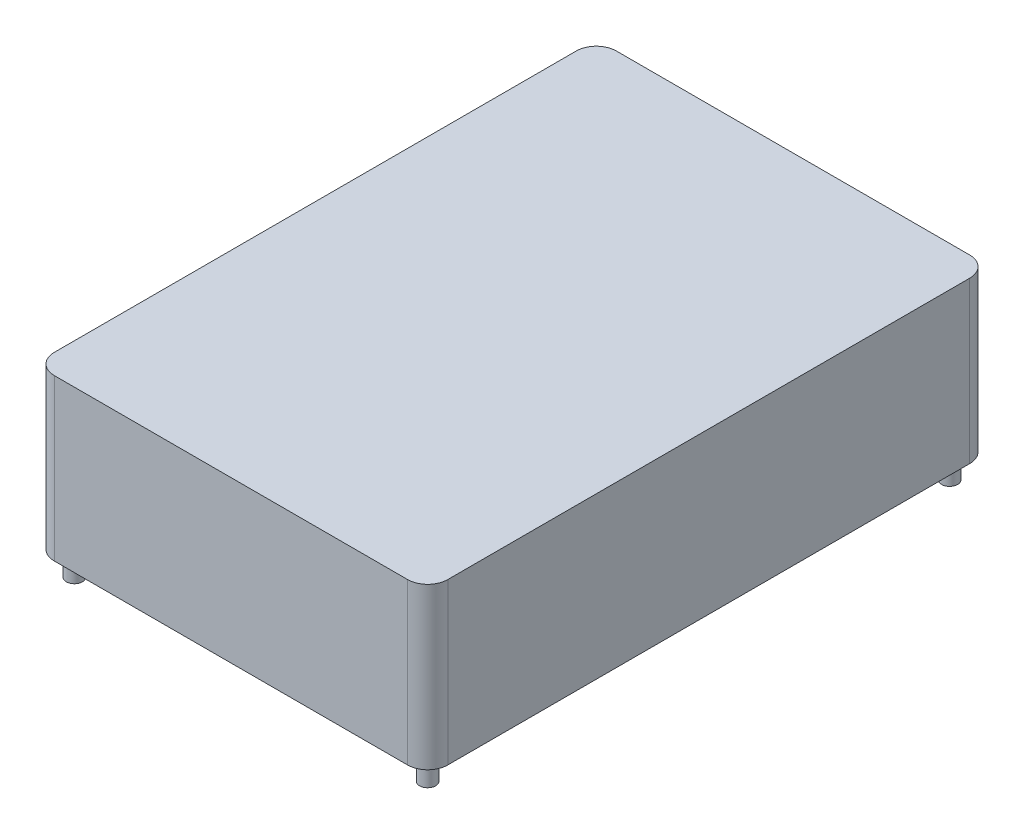
SolidWorks part; units mm, degrees
material "ABS"
ref_plane "Front Plane" through (0, 0, 0) normal (0, 0, 1) x (1, 0, 0)
ref_plane "Top Plane" through (0, 0, 0) normal (0, 1, 0) x (1, 0, 0)
ref_plane "Right Plane" through (0, 0, 0) normal (1, 0, 0) x (0, 0, -1)
sketch "Sketch1" plane through (0, 0, 0) normal (0, 1, 0) x (1, 0, 0)
  line L1 (-62.23, -88.9) -> (62.23, -88.9)
  line L2 (-62.23, -88.9) -> (-62.23, 88.9)
  line L3 (-62.23, 88.9) -> (62.23, 88.9)
  line L4 (62.23, -88.9) -> (62.23, 88.9)
  line L5 (-62.23, -88.9) -> (62.23, 88.9) construction
  line L6 (-62.23, 88.9) -> (62.23, -88.9) construction
  point P0 (0, 0)
  dimension "D1" = 124.46
  dimension "D2" = 177.8
extrude "Boss-Extrude1" add sketch "Sketch1" along normal blind 50.8
fillet "Fillet1" radius 6.35 4 edges at (62.23, 25.4, -88.9) (62.23, 25.4, 88.9) (-62.23, 25.4, 88.9) (-62.23, 25.4, -88.9)
sketch "Sketch3" plane through (0, 50.8, 0) normal (0, 1, 0) x (1, 0, 0)
  circle A0 centre (-55.88, 82.55) radius 6.35
  circle A1 centre (-55.88, 82.55) radius 2.54
  circle A2 centre (55.88, 82.55) radius 6.35
  circle A3 centre (55.88, 82.55) radius 2.54
  circle A4 centre (-55.88, -82.55) radius 6.35
  circle A5 centre (-55.88, -82.55) radius 2.54
  circle A6 centre (55.88, -82.55) radius 6.35
  circle A7 centre (55.88, -82.55) radius 2.54
  arc A8 (62.23, 82.55) -> (55.88, 88.9) centre (55.88, 82.55) ccw construction
  arc A9 (55.88, -88.9) -> (62.23, -82.55) centre (55.88, -82.55) ccw construction
  arc A10 (-55.88, 88.9) -> (-62.23, 82.55) centre (-55.88, 82.55) ccw construction
  arc A11 (-62.23, -82.55) -> (-55.88, -88.9) centre (-55.88, -82.55) ccw construction
  dimension "D1" = 5.08
  dimension "D2" = 12.7
  dimension "D3" = 5.08
  dimension "D4" = 12.7
  dimension "D5" = 5.08
  dimension "D6" = 12.7
  dimension "D7" = 5.08
  dimension "D8" = 12.7
extrude "Boss-Extrude2" add sketch "Sketch3" against normal blind 58.42 contours A1 | A3 | A5 | A7
